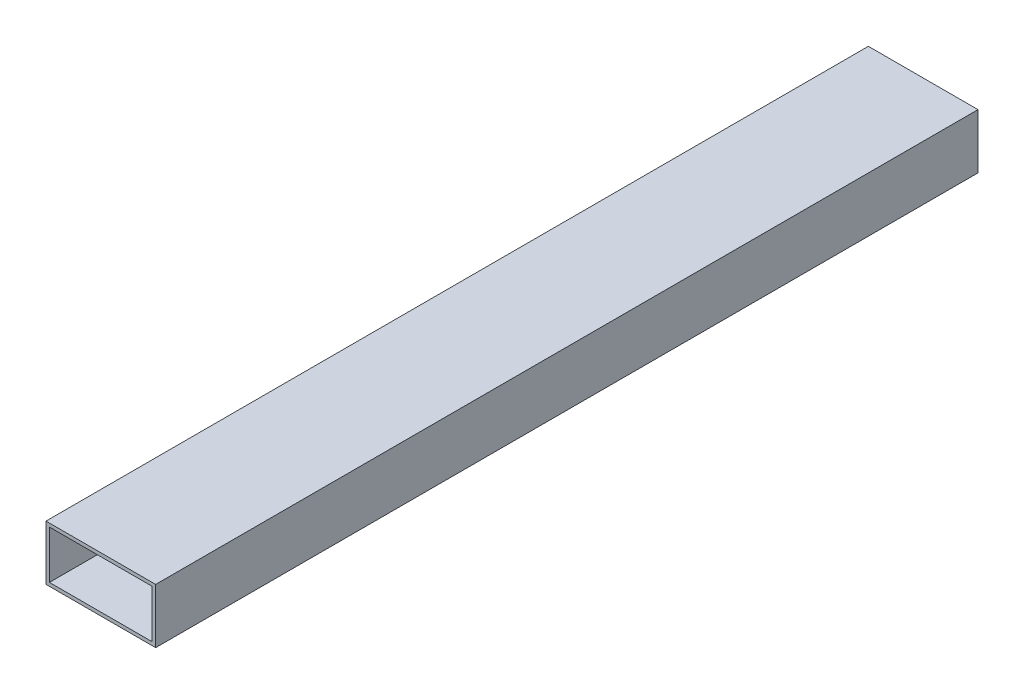
SolidWorks part; units mm, degrees
ref_plane "Front Plane" through (0, 0, 0) normal (0, 0, 1) x (1, 0, 0)
ref_plane "Top Plane" through (0, 0, 0) normal (0, 1, 0) x (1, 0, 0)
ref_plane "Right Plane" through (0, 0, 0) normal (1, 0, 0) x (0, 0, -1)
sketch "Sketch1" plane through (0, 0, 0) normal (0, 0, 1) x (1, 0, 0)
  line L1 (23.8125, -11.1125) -> (-23.8125, -11.1125)
  line L2 (23.8125, -11.1125) -> (23.8125, 11.1125)
  line L3 (23.8125, 11.1125) -> (-23.8125, 11.1125)
  line L4 (-23.8125, -11.1125) -> (-23.8125, 11.1125)
  line L5 (23.8125, -11.1125) -> (-23.8125, 11.1125) construction
  line L6 (23.8125, 11.1125) -> (-23.8125, -11.1125) construction
  line L7 (25.4, -12.7) -> (-25.4, -12.7)
  line L8 (25.4, -12.7) -> (25.4, 12.7)
  line L9 (25.4, 12.7) -> (-25.4, 12.7)
  line L10 (-25.4, -12.7) -> (-25.4, 12.7)
  line L11 (25.4, -12.7) -> (-25.4, 12.7) construction
  line L12 (25.4, 12.7) -> (-25.4, -12.7) construction
  point P0 (0, 0)
  point P6 (0, 0)
  dimension "D1" = 50.8
  dimension "D2" = 25.4
  dimension "D3" = 1.5875
  dimension "D4" = 1.5875
extrude "Boss-Extrude1" add sketch "Sketch1" along normal blind 381
